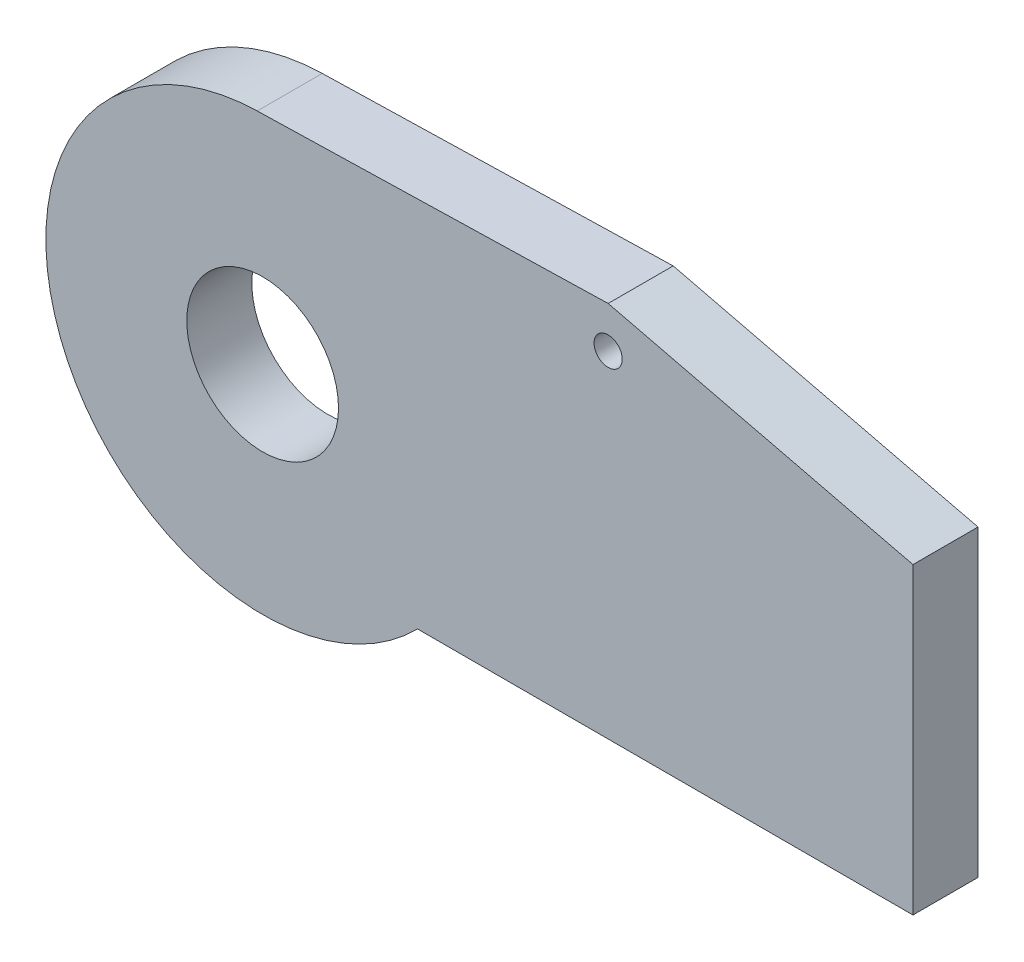
SolidWorks part; units mm, degrees
material "Maple"
ref_plane "Front Plane" through (0, 0, 0) normal (0, 0, 1) x (1, 0, 0)
ref_plane "Top Plane" through (0, 0, 0) normal (0, 1, 0) x (1, 0, 0)
ref_plane "Right Plane" through (0, 0, 0) normal (1, 0, 0) x (0, 0, -1)
sketch "Sketch1" plane through (0, 0, 0) normal (0, 0, 1) x (1, 0, 0)
  line L0 (149.9999, 70.0001) -> (79.6941, 87.0053)
  line L1 (35.707, 0.0001) -> (149.9999, 0.0001)
  line L4 (149.9999, 0.0001) -> (149.9999, 70.0001)
  line L5 (79.6941, 87.0053) -> (-1.248, 84.9845)
  arc A0 (-1.248, 84.9845) -> (35.707, 0.0001) centre (-0.0001, 35.0001) ccw
  circle A1 centre (-0.0001, 35.0001) radius 17.5
  circle A2 centre (79.6941, 77.4794) radius 3.25
  point P7 (35.707, 101.9757)
  point P11 (0, 0)
  point P12 (0, 0)
  point P13 (35.707, 97.894)
  point P14 (79.6941, 87.0053)
  point P15 (79.6941, 70.0001)
  point P16 (0, 0)
  point P17 (79.6941, 77.4794)
  dimension "D2" = 100
  dimension "D1" = 35
  dimension "D3" = 6.5
extrude "Boss-Extrude1" add sketch "Sketch1" along normal blind 15
